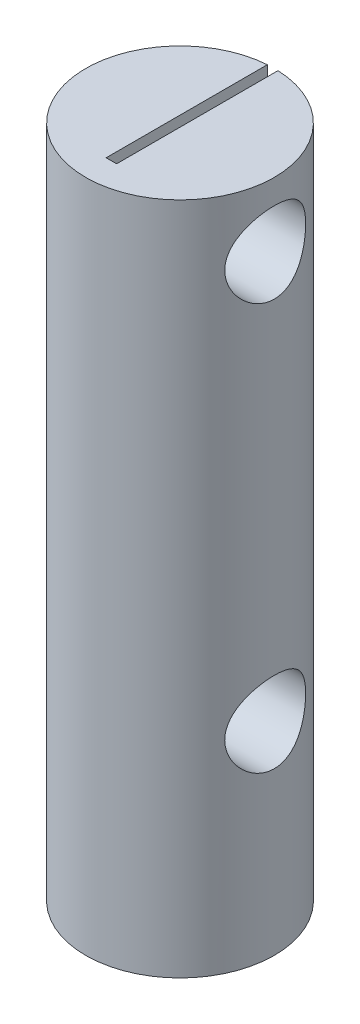
SolidWorks part; units mm, degrees
ref_plane "Front Plane" through (0, 0, 0) normal (0, 0, 1) x (1, 0, 0)
ref_plane "Top Plane" through (0, 0, 0) normal (0, 1, 0) x (1, 0, 0)
ref_plane "Right Plane" through (0, 0, 0) normal (1, 0, 0) x (0, 0, -1)
sketch "Sketch1" plane through (0, 0, 0) normal (0, 1, 0) x (1, 0, 0)
  circle A0 centre (0, 0) radius 7
  dimension "D1" = 14
extrude "Boss-Extrude1" add sketch "Sketch1" along normal blind 50
sketch "Sketch2" plane through (0, 50, 0) normal (0, 1, 0) x (1, 0, 0)
  line L0 (0, 0) -> (7.1226, 0) construction
  line L1 (7.1226, 0) -> (-7.4051, 0) construction
  line L2 (-7.4051, 0) -> (-0.1412, 0) construction
  line L3 (-0.1412, 0) -> (-0.1412, 6.9986) construction
  line L4 (-0.1412, 6.9986) -> (-0.1412, -7.617) construction
  line L5 (6.7761, 0) -> (6.7761, 6.2955) construction
  line L6 (-0.5, 7.4036) -> (0.2761, 7.4036)
  line L7 (-0.5, 7.4036) -> (-0.5, -4.9799)
  line L8 (-0.5, -4.9799) -> (0.2761, -4.9799)
  line L9 (0.2761, 7.4036) -> (0.2761, -4.9799)
  line L10 (6.7761, 6.2955) -> (6.7761, -3.4144) construction
  line L11 (-7, 0) -> (-7, 6.2955) construction
  line L12 (-7, 6.2955) -> (-7, -7.617) construction
  line L13 (-0.1412, -6.9799) -> (-7.2013, -6.9799) construction
  line L14 (-7.2013, -6.9799) -> (8.3265, -6.9799) construction
  circle A0 centre (0, 0) radius 7 construction
  point P19 (-0.112, -4.9799)
  dimension "D1" = 6.5
  dimension "D2" = 6.5
  dimension "D3" = 2
extrude "Cut-Extrude1" cut sketch "Sketch2" against normal blind 100
sketch "Sketch3" plane through (0, 0, 0) normal (1, 0, 0) x (0, 0, -1)
  line L0 (-0.0027, 15) -> (-0.0027, -18.7828) construction
  line L1 (-0.0027, -18.7828) -> (-0.0027, 23.7628) construction
  line L2 (11.2967, 15) -> (-12.0516, 15) construction
  line L3 (-7, 0) -> (6.9946, 0) construction
  line L4 (0, 0) -> (0, 60.1799) construction
  line L5 (0, 60.1799) -> (0, 30.09) construction
  line L6 (0, 30.09) -> (-10.7758, 30.09) construction
  line L7 (-10.7758, 30.09) -> (28.9416, 30.09) construction
  circle A0 centre (-0.0027, 15) radius 3
  circle A1 centre (-0.0027, 45.1799) radius 3
  dimension "D1" = 6
  dimension "D2" = 15
extrude "Cut-Extrude2" cut sketch "Sketch3" against normal blind 40 and the other way blind 40
